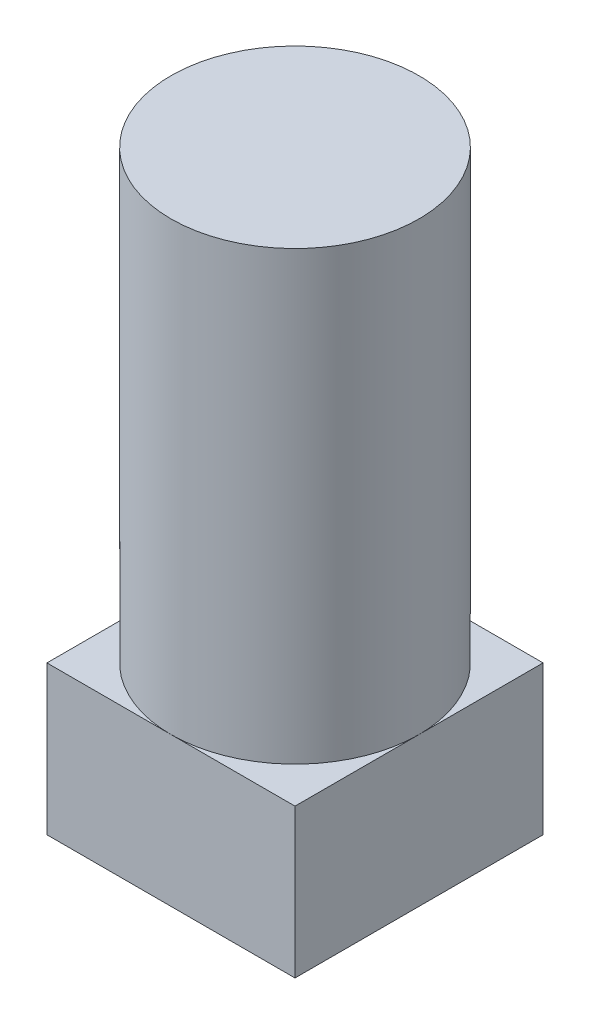
SolidWorks part; units mm, degrees
ref_plane "Front Plane" through (0, 0, 0) normal (0, 0, 1) x (1, 0, 0)
ref_plane "Top Plane" through (0, 0, 0) normal (0, 1, 0) x (1, 0, 0)
ref_plane "Right Plane" through (0, 0, 0) normal (1, 0, 0) x (0, 0, -1)
sketch "Sketch2" plane through (0, 0, 0) normal (0, 1, 0) x (1, 0, 0)
  line L1 (-127, -127) -> (127, -127)
  line L2 (-127, -127) -> (-127, 127)
  line L3 (-127, 127) -> (127, 127)
  line L4 (127, -127) -> (127, 127)
  line L5 (-127, -127) -> (127, 127) construction
  line L6 (-127, 127) -> (127, -127) construction
  point P0 (0, 0)
  dimension "D1" = 254
  dimension "D2" = 254
extrude "Boss-Extrude1" add sketch "Sketch2" along normal blind 152.4 contours L2 L1 L4 L3
sketch "Sketch3" plane through (0, 152.4, 0) normal (0, 1, 0) x (1, 0, 0)
  circle A0 centre (0, 0) radius 127
extrude "Boss-Extrude2" add sketch "Sketch3" along normal blind 457.2
